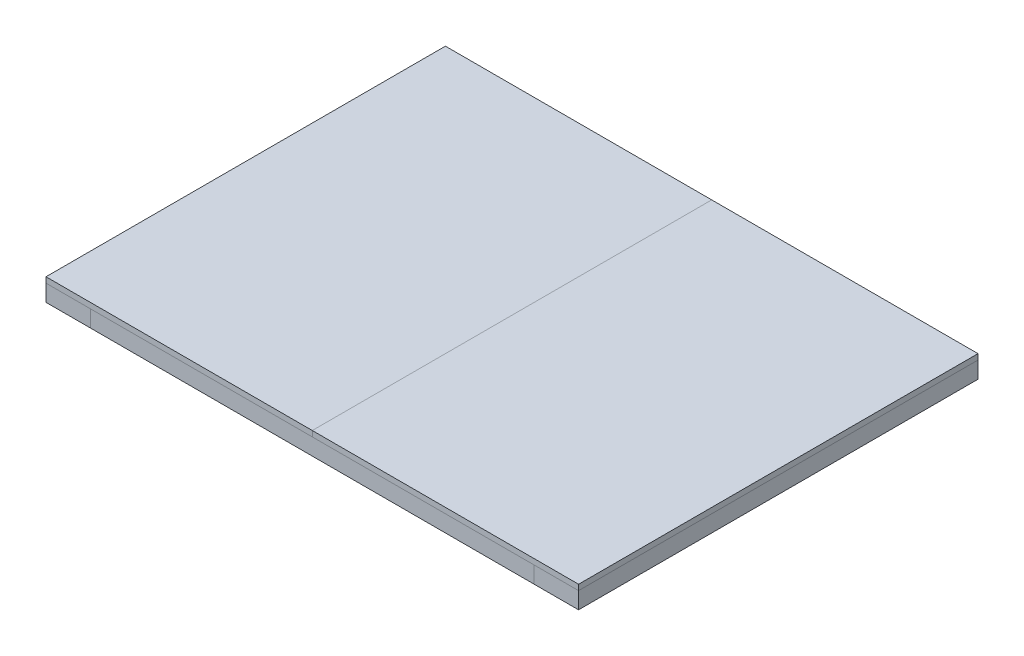
SolidWorks part; units mm, degrees
material "Oak"
ref_plane "Front Plane" through (0, 0, 0) normal (0, 0, 1) x (1, 0, 0)
ref_plane "Top Plane" through (0, 0, 0) normal (0, 1, 0) x (1, 0, 0)
ref_plane "Right Plane" through (0, 0, 0) normal (1, 0, 0) x (0, 0, -1)
sketch "Sketch1" plane through (0, 0, 0) normal (0, 1, 0) x (1, 0, 0)
  line L1 (0, 0) -> (609.6, 0)
  line L2 (0, 0) -> (0, 914.4)
  line L3 (0, 914.4) -> (609.6, 914.4)
  line L4 (609.6, 0) -> (609.6, 914.4)
  dimension "D1" = 609.6
  dimension "D2" = 914.4
extrude "Boss-Extrude1" add sketch "Sketch1" along normal blind 12.7
sketch "Sketch2" plane through (0, 0, 0) normal (0, 1, 0) x (1, 0, 0)
  line L1 (609.6, 0) -> (1219.2, 0)
  line L2 (609.6, 0) -> (609.6, 914.4)
  line L3 (609.6, 914.4) -> (1219.2, 914.4)
  line L4 (1219.2, 0) -> (1219.2, 914.4)
  dimension "D1" = 609.6
  dimension "D2" = 914.4
extrude "Boss-Extrude2" add sketch "Sketch2" along normal blind 12.7 separate body
ref_plane "Plane1" through (0, 0, 0) normal (0, -1, 0) x (-1, 0, 0)
sketch "Sketch3" plane through (0, 0, 0) normal (0, -1, 0) x (-1, 0, 0)
  line L5 (-609.6, 0) -> (-1219.2, 0) construction
  line L6 (-1219.2, 914.4) -> (-1117.6, 914.4)
  line L7 (-1219.2, 914.4) -> (-1219.2, 0)
  line L8 (-1219.2, 0) -> (-1117.6, 0)
  line L9 (-1117.6, 914.4) -> (-1117.6, 0)
  dimension "D2" = 101.6
sketch "Sketch5" plane through (0, 0, 0) normal (0, -1, 0) x (-1, 0, 0)
  line L0 (0, 0) -> (-609.6, 0) construction
  line L1 (0, 914.4) -> (-101.6, 914.4)
  line L2 (0, 914.4) -> (0, 0)
  line L3 (0, 0) -> (-101.6, 0)
  line L4 (-101.6, 914.4) -> (-101.6, 0)
  dimension "D1" = 101.6
sketch "Sketch6" plane through (0, 0, 0) normal (0, -1, 0) x (-1, 0, 0)
  line L0 (-101.6, 914.4) -> (-101.6, 0) construction
  line L1 (-1117.6, 914.4) -> (-101.6, 914.4)
  line L2 (-1117.6, 914.4) -> (-1117.6, 812.8)
  line L3 (-1117.6, 812.8) -> (-101.6, 812.8)
  line L4 (-101.6, 914.4) -> (-101.6, 812.8)
  dimension "D1" = 101.6
sketch "Sketch7" plane through (0, 0, 0) normal (0, -1, 0) x (-1, 0, 0)
  line L0 (-101.6, 914.4) -> (-101.6, 0) construction
  line L1 (-1117.6, 0) -> (-101.6, 0)
  line L2 (-1117.6, 0) -> (-1117.6, 101.6)
  line L3 (-1117.6, 101.6) -> (-101.6, 101.6)
  line L4 (-101.6, 0) -> (-101.6, 101.6)
  dimension "D1" = 101.6
sketch "Sketch8" plane through (0, 0, 0) normal (0, -1, 0) x (-1, 0, 0)
  line L0 (-1117.6, 812.8) -> (-101.6, 812.8) construction
  line L1 (-660.4, 812.8) -> (-558.8, 812.8)
  line L2 (-660.4, 812.8) -> (-660.4, 101.6)
  line L3 (-660.4, 101.6) -> (-558.8, 101.6)
  line L4 (-558.8, 812.8) -> (-558.8, 101.6)
  line L5 (-1117.6, 101.6) -> (-101.6, 101.6) construction
  line L6 (-609.6, 0) -> (-609.6, 914.4) construction
  dimension "D1" = 50.8
  dimension "D2" = 101.6
extrude "Boss-Extrude4" add sketch "Sketch3" along normal blind 38.1 separate body
extrude "Boss-Extrude5" add sketch "Sketch5" along normal blind 38.1 separate body
extrude "Boss-Extrude6" add sketch "Sketch7" along normal blind 38.1 separate body
extrude "Boss-Extrude7" add sketch "Sketch6" along normal blind 38.1 separate body
extrude "Boss-Extrude8" add sketch "Sketch8" along normal blind 38.1 separate body
